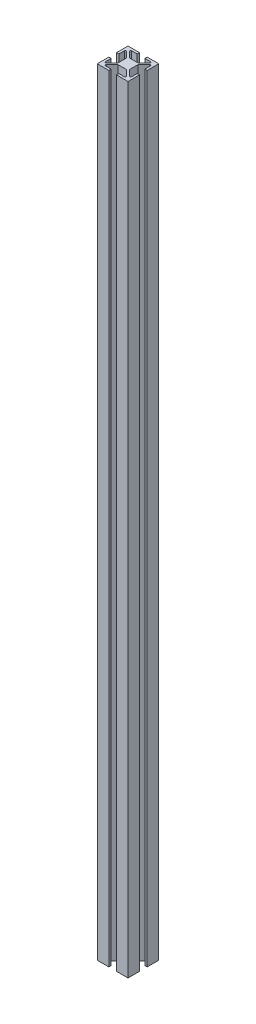
SolidWorks part; units mm, degrees
ref_plane "Plan de face" through (0, 0, 0) normal (0, 0, 1) x (1, 0, 0)
ref_plane "Plan de dessus" through (0, 0, 0) normal (0, 1, 0) x (1, 0, 0)
ref_plane "Plan de droite" through (0, 0, 0) normal (1, 0, 0) x (0, 0, -1)
sketch "Esquisse1" plane through (0, 0, 0) normal (0, 1, 0) x (1, 0, 0)
  line L0 (6.1245, 16.1036) -> (30.6226, 16.1036) construction
  line L6 (-11.5924, 0) -> (12.1076, 0) construction
  line L7 (0, 12.3466) -> (0, -12.7449) construction
  line L12 (-10, -10) -> (10, 10) construction
  line L59 (-10, -2.5) -> (-10, -10)
  line L60 (-10, -2.5) -> (-8.5, -2.5)
  line L69 (-8.5, -2.5) -> (-8.5, -6.2322)
  line L70 (-7.6464, -6.5858) -> (-3.75, -2.6893)
  line L73 (-6.5858, -7.6464) -> (-2.6893, -3.75)
  line L74 (-2.5, -8.5) -> (-6.2322, -8.5)
  line L75 (-2.5, -10) -> (-2.5, -8.5)
  line L76 (-2.5, -10) -> (-10, -10)
  line L77 (-2.5, 10) -> (-2.5, 8.5)
  line L78 (-2.5, 10) -> (-10, 10)
  line L79 (-10, 2.5) -> (-10, 10)
  line L80 (-10, 2.5) -> (-8.5, 2.5)
  line L81 (-8.5, 2.5) -> (-8.5, 6.2322)
  line L82 (-7.6464, 6.5858) -> (-3.75, 2.6893)
  line L83 (-6.5858, 7.6464) -> (-2.6893, 3.75)
  line L84 (-2.5, 8.5) -> (-6.2322, 8.5)
  line L85 (10, 2.5) -> (8.5, 2.5)
  line L86 (10, 2.5) -> (10, 10)
  line L87 (2.5, 10) -> (10, 10)
  line L88 (2.5, 10) -> (2.5, 8.5)
  line L89 (2.5, 8.5) -> (6.2322, 8.5)
  line L90 (6.5858, 7.6464) -> (2.6893, 3.75)
  line L91 (7.6464, 6.5858) -> (3.75, 2.6893)
  line L92 (8.5, 2.5) -> (8.5, 6.2322)
  line L93 (2.5, -10) -> (2.5, -8.5)
  line L94 (2.5, -10) -> (10, -10)
  line L95 (10, -2.5) -> (10, -10)
  line L96 (10, -2.5) -> (8.5, -2.5)
  line L97 (8.5, -2.5) -> (8.5, -6.2322)
  line L98 (7.6464, -6.5858) -> (3.75, -2.6893)
  line L99 (6.5858, -7.6464) -> (2.6893, -3.75)
  line L100 (2.5, -8.5) -> (6.2322, -8.5)
  line L101 (-3.75, 2.6893) -> (-3.75, -2.6893)
  line L102 (-2.6893, -3.75) -> (2.6893, -3.75)
  line L103 (-2.6893, 3.75) -> (2.6893, 3.75)
  line L104 (3.75, 2.6893) -> (3.75, -2.6893)
  arc A0 (-8.5, 6.2322) -> (-7.6464, 6.5858) centre (-8, 6.2322) cw
  arc A1 (-8.5, -6.2322) -> (-7.6464, -6.5858) centre (-8, -6.2322) ccw
  arc A2 (-6.5858, -7.6464) -> (-6.2322, -8.5) centre (-6.2322, -8) ccw
  arc A3 (6.5858, -7.6464) -> (6.2322, -8.5) centre (6.2322, -8) cw
  arc A4 (8.5, -6.2322) -> (7.6464, -6.5858) centre (8, -6.2322) cw
  arc A5 (7.6464, 6.5858) -> (8.5, 6.2322) centre (8, 6.2322) cw
  arc A6 (6.2322, 8.5) -> (6.5858, 7.6464) centre (6.2322, 8) cw
  arc A7 (-6.5858, 7.6464) -> (-6.2322, 8.5) centre (-6.2322, 8) cw
  point P7 (-2.5, -9.25)
  point P8 (2.5, -9.25)
  point P15 (-8.5, -7.4393)
  point P51 (0, 0)
  point P52 (-7.4393, -8.5)
  dimension "D2" = 5
  dimension "D7" = 0.5
  dimension "D1" = 20
  dimension "D3" = 4
  dimension "D4" = 7.5
  dimension "D5" = 1.5
  dimension "D6" = 1.5
extrude "Boss.-Extru.1" add sketch "Esquisse1" along normal blind 505
